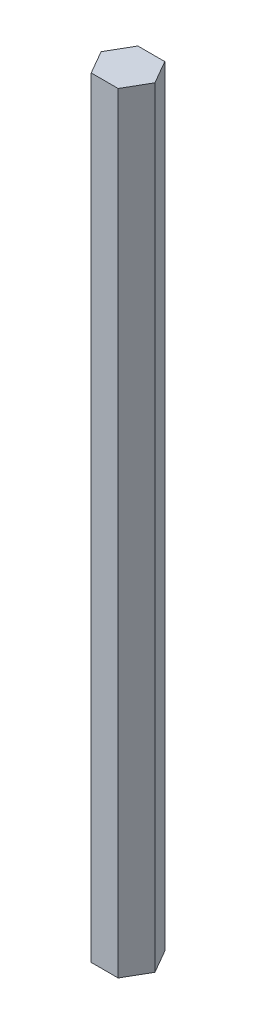
SolidWorks part; units mm, degrees
ref_plane "Front Plane" through (0, 0, 0) normal (0, 0, 1) x (1, 0, 0)
ref_plane "Top Plane" through (0, 0, 0) normal (0, 1, 0) x (1, 0, 0)
ref_plane "Right Plane" through (0, 0, 0) normal (1, 0, 0) x (0, 0, -1)
sketch "Sketch1" plane through (0, 0, 0) normal (0, 1, 0) x (1, 0, 0)
  line L1 (2.0975, 3.633) -> (-2.0975, 3.633)
  line L2 (-2.0975, 3.633) -> (-4.195, 0)
  line L3 (-4.195, 0) -> (-2.0975, -3.633)
  line L4 (-2.0975, -3.633) -> (2.0975, -3.633)
  line L5 (2.0975, -3.633) -> (4.195, 0)
  line L6 (4.195, 0) -> (2.0975, 3.633)
  circle A0 centre (0, 0) radius 3.633 construction
  dimension "D1" = 8.39
extrude "Boss-Extrude1" add sketch "Sketch1" against normal blind 120
